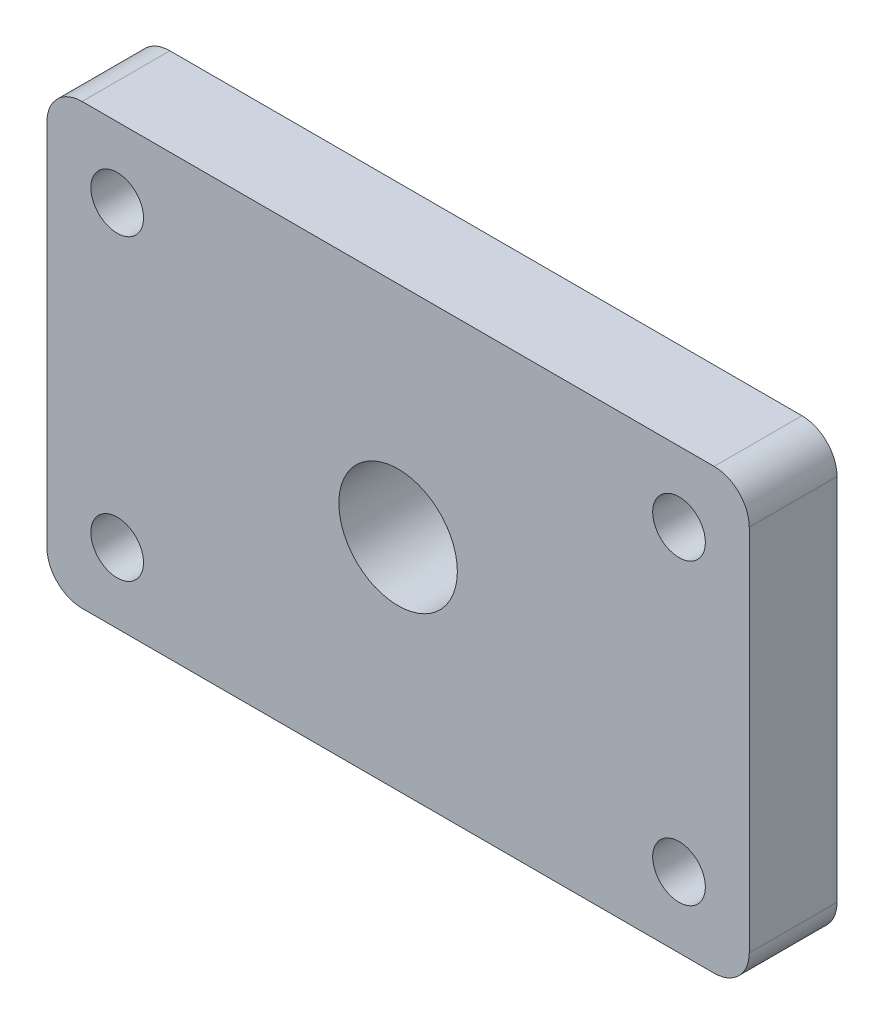
SolidWorks part; units mm, degrees
ref_plane "Front Plane" through (0, 0, 0) normal (0, 0, 1) x (1, 0, 0)
ref_plane "Top Plane" through (0, 0, 0) normal (0, 1, 0) x (1, 0, 0)
ref_plane "Right Plane" through (0, 0, 0) normal (1, 0, 0) x (0, 0, -1)
sketch "Model" plane through (0, 0, 0) normal (0, 0, 1) x (1, 0, 0)
  line L0 (-36, -25) -> (36, -25)
  line L1 (-40, 21) -> (-40, -21)
  line L2 (36, 25) -> (-36, 25)
  line L3 (40, -21) -> (40, 21)
  circle A0 centre (-32, 17) radius 3
  circle A1 centre (32, -17) radius 3
  circle A2 centre (32, 17) radius 3
  circle A3 centre (-32, -17) radius 3
  circle A4 centre (0, 0) radius 6.75
  arc A5 (-40, -21) -> (-36, -25) centre (-36, -21) ccw
  arc A6 (-36, 25) -> (-40, 21) centre (-36, 21) ccw
  arc A7 (40, 21) -> (36, 25) centre (36, 21) ccw
  arc A8 (36, -25) -> (40, -21) centre (36, -21) ccw
extrude "Boss-Extrude1" add sketch "Model" along normal blind 10
sketch "Sketch2" plane through (0, 0, 10) normal (0, 0, 1) x (1, 0, 0)
  text T0 "Copyright © Adarsh Belavatagi and Manikanta Pujar 2018.\r\nThis documentation describes Open Hardware and is licensed under the CERN OHL v. 1.2.\r\nYou may redistribute and modify this documentation under the terms of the CERN OHL v.1.2.\r\n(http://ohwr.org/cernohl). This documentation is distributed WITHOUT ANY EXPRESS OR\r\nIMPLIED WARRANTY, INCLUDING OF MERCHANTABILITY, SATISFACTORY QUALITY AND FITNESS FOR A PARTICULAR PURPOSE.\r\nPlease see the CERN OHL v.1.2 for applicable conditions\r\n\r\nThe full text of the license is available in LICENSE.txt(https://github.com/AdarshBelavatagi/Maudslay/blob/master/LICENSE.txt)\r\n"
